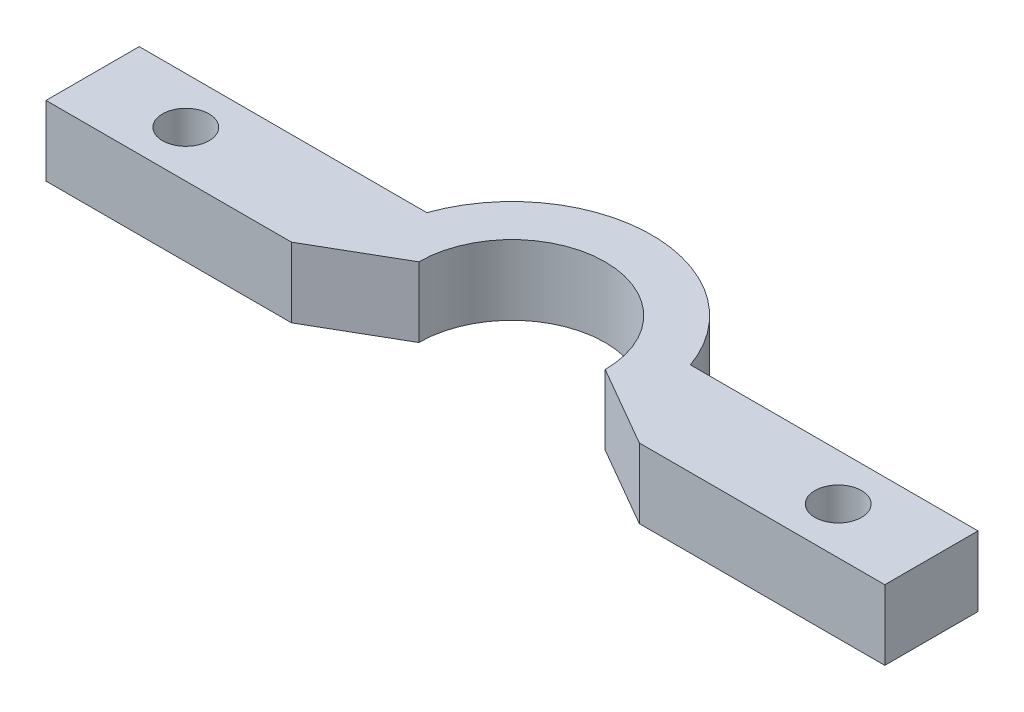
SolidWorks part; units mm, degrees
ref_plane "Front Plane" through (0, 0, 0) normal (0, 0, 1) x (1, 0, 0)
ref_plane "Top Plane" through (0, 0, 0) normal (0, 1, 0) x (1, 0, 0)
ref_plane "Right Plane" through (0, 0, 0) normal (1, 0, 0) x (0, 0, -1)
sketch "Sketch1" plane through (0, 0, 0) normal (0, 1, 0) x (1, 0, 0)
  line L0 (0, 0) -> (4.7625, 0)
  line L1 (-14.2875, -1.5875) -> (14.2875, -1.5875)
  line L2 (-14.2875, -1.5875) -> (-14.2875, 1.5875)
  line L3 (-14.2875, 1.5875) -> (14.2875, 1.5875)
  line L4 (14.2875, -1.5875) -> (14.2875, 1.5875)
  line L5 (-14.2875, -1.5875) -> (14.2875, 1.5875) construction
  line L6 (-14.2875, 1.5875) -> (14.2875, -1.5875) construction
  line L7 (4.7625, 0) -> (-4.7625, 0)
  line L8 (-3.175, 0) -> (-5.9246, -1.5875)
  line L9 (-5.9246, -1.5875) -> (5.9246, -1.5875)
  line L10 (5.9246, -1.5875) -> (3.175, 0)
  circle A0 centre (0, 0) radius 4.7625
  circle A1 centre (0, 0) radius 3.175
  circle A2 centre (-11.1125, 0) radius 0.7937
  circle A3 centre (11.1125, 0) radius 0.7937
  point P0 (0, 0)
  dimension "D3" = 1.5875
  dimension "D4" = 9.525
  dimension "D6" = 1.5875
  dimension "D7" = 3.175
  dimension "D1" = 28.575
  dimension "D2" = 3.175
  dimension "D5" = 3.175
  dimension "D8" = 3.175
extrude "Boss-Extrude1" add sketch "Sketch1" along normal mid plane 2.3813
